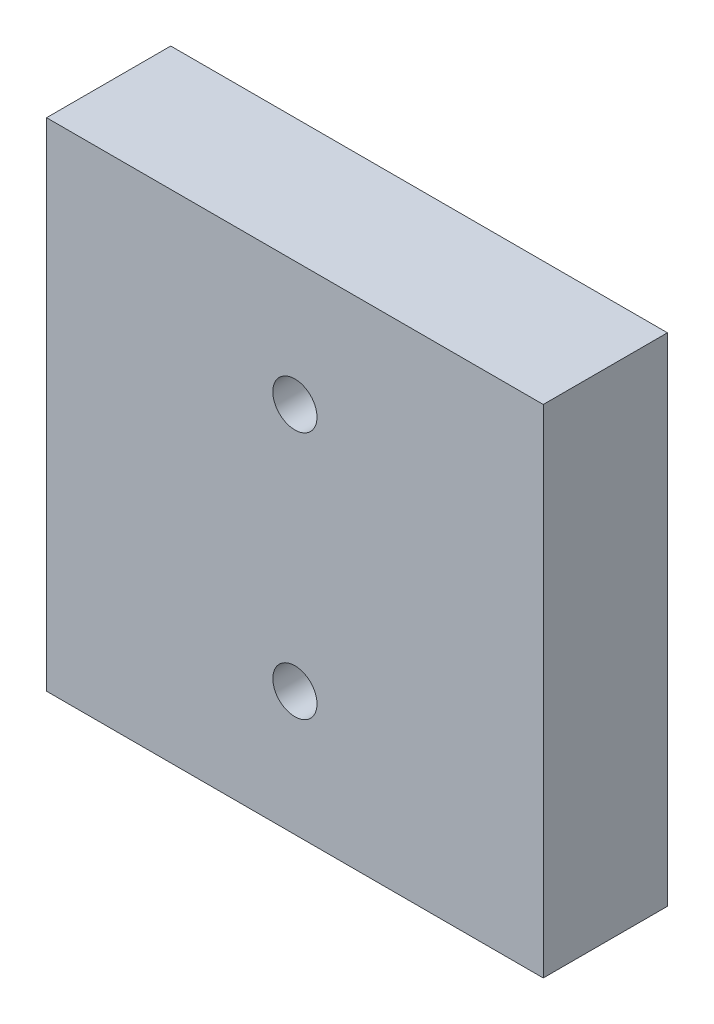
SolidWorks part; units mm, degrees
ref_plane "Front Plane" through (0, 0, 0) normal (0, 0, 1) x (1, 0, 0)
ref_plane "Top Plane" through (0, 0, 0) normal (0, 1, 0) x (1, 0, 0)
ref_plane "Right Plane" through (0, 0, 0) normal (1, 0, 0) x (0, 0, -1)
sketch "Sketch1" plane through (0, 0, 0) normal (0, 0, 1) x (1, 0, 0)
  line L1 (0, 0) -> (25.4, 0)
  line L2 (0, 0) -> (0, 25.4)
  line L3 (0, 25.4) -> (25.4, 25.4)
  line L4 (25.4, 0) -> (25.4, 25.4)
  dimension "D1" = 25.4
  dimension "D2" = 25.4
extrude "Boss-Extrude1" add sketch "Sketch1" along normal blind 6.35
hole_wizard "#43 (0.089) Diameter Hole1" positions "Sketch3" profile "Sketch4" hole size "#43" standard "ANSI Inch" end condition up to next
sketch "Sketch3" plane through (0, 0, 0) normal (0, 0, -1) x (-1, 0, 0)
  line L0 (0, 0) -> (-25.4, 0) construction
  line L1 (-25.4, 0) -> (-25.4, 25.4) construction
  line L2 (-25.4, 25.4) -> (0, 25.4) construction
  point P0 (-12.7, 6.35)
  point P2 (-12.7, 19.05)
  dimension "D1" = 6.35
  dimension "D2" = 12.7
  dimension "D3" = 6.35
  dimension "D4" = 12.7
sketch "Sketch4" plane through (12.7, 6.35, 0) normal (1, 0, 0) x (0, 1, 0)
  line L0 (0, 0) -> (0, 6.35)
  line L1 (0, 6.35) -> (1.1303, 6.35)
  line L2 (1.1303, 6.35) -> (1.1303, 0)
  line L5 (1.1303, 0) -> (0, 0)
  line L11 (0, -6.35) -> (0, 107.95) construction
  dimension "Thru Hole Dia." = 2.2606
  dimension "Thru Hole Depth" = 6.35
